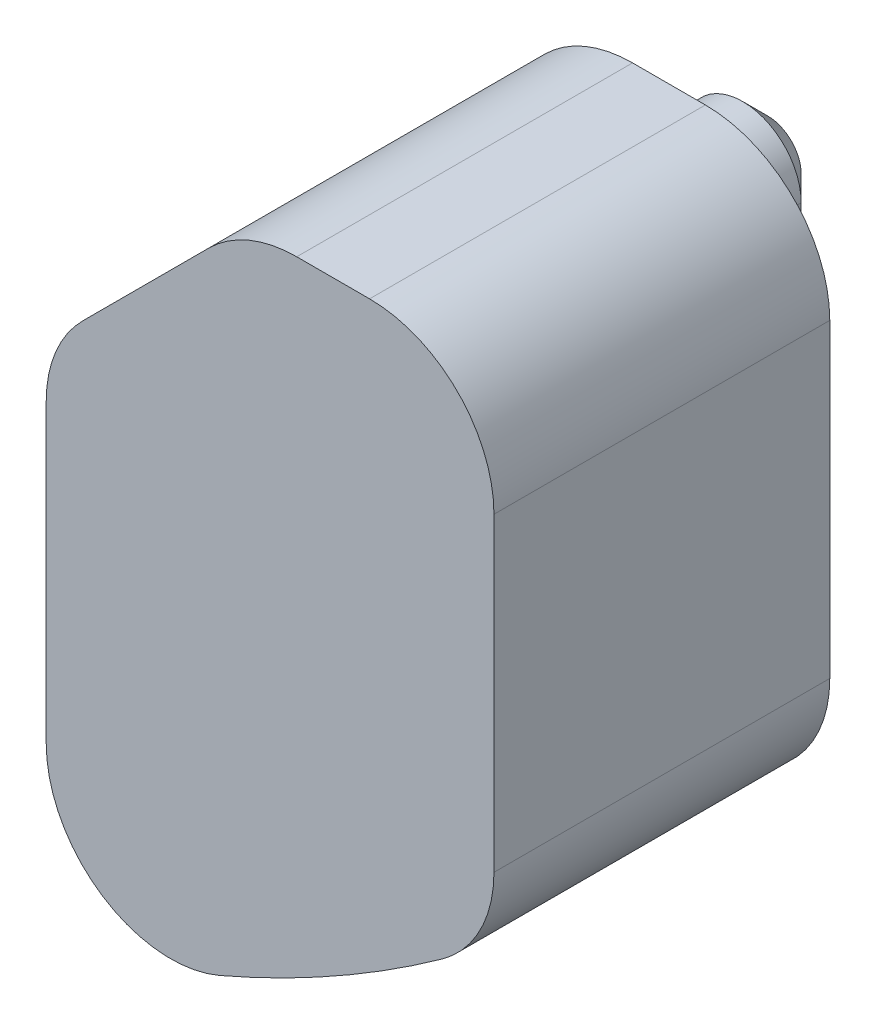
SolidWorks part; units mm, degrees
ref_plane "Front Plane" through (0, 0, 0) normal (0, 0, 1) x (1, 0, 0)
ref_plane "Top Plane" through (0, 0, 0) normal (0, 1, 0) x (1, 0, 0)
ref_plane "Right Plane" through (0, 0, 0) normal (1, 0, 0) x (0, 0, -1)
sketch "Sketch1" plane through (0, 0, 0) normal (0, 0, 1) x (1, 0, 0)
  line L0 (6, -23.2379) -> (6, -12.7602)
  line L1 (6, -12.7602) -> (10, -8.7602)
  line L2 (10, -8.7602) -> (15, -8.7602)
  line L3 (15, -8.7602) -> (15, -18.735)
  line L4 (4, -12.7602) -> (10.3512, -12.7602) construction
  line L5 (3.7103, -12.7602) -> (-1, -12.7602) construction
  line L6 (12, -19) -> (12, -12) construction
  line L8 (4, -20.5602) -> (4, -13.5602) construction
  arc A0 (15, -18.735) -> (6, -23.2379) centre (0, 0) cw
  arc A1 (1.5, -22.7506) -> (8.8815, 20.999) centre (0, 0) ccw construction
  circle A2 centre (0, 0) radius 24 construction
  dimension "D2" = 2
  dimension "D1" = 135
  dimension "D3" = 3
  dimension "D4" = 5
extrude "body" add sketch "Sketch1" along normal up to surface (6.75 mm away)
fillet "Fillet1" radius 2.5 5 edges at (6, -12.7602, 3.375) (10, -8.7602, 3.375) (15, -8.7602, 3.375) (15, -18.735, 3.375) (6, -23.2379, 3.375)
hole_wizard "9/64 (0.14063) Diameter Hole1" positions "Sketch2" profile "Sketch3" hole size "9/64" standard "ANSI Inch"
sketch "Sketch2" plane through (6, 0, 0) normal (-1, 0, 0) x (0, 0, 1)
  point P0 (4, -17.0602)
sketch "Sketch3" plane through (6, -17.0602, 4) normal (0, 1, 0) x (0, 0, 1)
  line L0 (0, 0) -> (0, 8.0731)
  line L1 (0, 8.0731) -> (1.786, 7)
  line L2 (1.786, 7) -> (1.786, 1.533)
  line L3 (1.786, 1.533) -> (2.421, 0)
  line L5 (2.421, 0) -> (0, 0)
  line L6 (-1.786, 1.533) -> (-2.421, 0) construction
  line L10 (0, 8.0731) -> (-1.786, 7) construction
  line L11 (0, -6.35) -> (0, 107.95) construction
  dimension "Hole Dia." = 3.572
  dimension "Hole Depth" = 7
  dimension "Near C'Sink Dia." = 4.842
  dimension "Near C'Sink Angle" = 45
  dimension "Drill Angle" = 118
sketch "Sketch4" plane through (0, 0, 0) normal (0, 0, -1) x (-1, 0, 0)
  line L0 (-9.575, -19) -> (-9.575, -12)
  line L1 (-11.925, -19) -> (-11.925, -12)
  line L2 (-12, -12) -> (-12, -19) construction
  arc A0 (-9.575, -19) -> (-11.925, -19) centre (-10.75, -19) cw
  arc A1 (-9.575, -12) -> (-11.925, -12) centre (-10.75, -12) ccw
  arc A2 (-12, -19) -> (-11.922, -19.4347) centre (-10.75, -19) ccw construction
  arc A3 (-9.5, -12) -> (-12, -12) centre (-10.75, -12) ccw construction
  dimension "D1" = 0.075
extrude "mount peg" add sketch "Sketch4" along normal up to surface (3 mm away)
chamfer "peg chamfer" distance 0.5 angle 45 4 edges at (10.75, -20.175, -3) (11.925, -15.5, -3) (10.75, -10.825, -3) (9.575, -15.5, -3)
